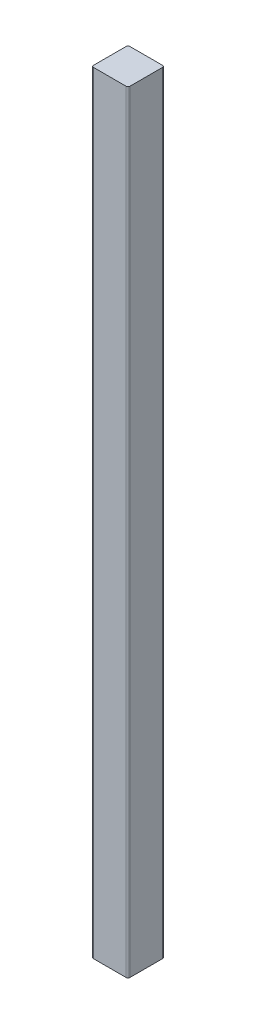
SolidWorks part; units mm, degrees
material "6063-O, Extruded Rod (SS)"
ref_plane "Front Plane" through (0, 0, 0) normal (0, 0, 1) x (1, 0, 0)
ref_plane "Top Plane" through (0, 0, 0) normal (0, 1, 0) x (1, 0, 0)
ref_plane "Right Plane" through (0, 0, 0) normal (1, 0, 0) x (0, 0, -1)
sketch "Sketch1" plane through (0, 0, 0) normal (0, 1, 0) x (1, 0, 0)
  line L1 (-18, 20) -> (18, 20)
  line L2 (-20, 18) -> (-20, -18)
  line L3 (-18, -20) -> (18, -20)
  line L4 (20, 18) -> (20, -18)
  line L5 (-20, 20) -> (20, -20) construction
  line L6 (-20, -20) -> (20, 20) construction
  arc A0 (-20, -18) -> (-18, -20) centre (-18, -18) ccw
  arc A1 (18, -20) -> (20, -18) centre (18, -18) ccw
  arc A2 (18, 20) -> (20, 18) centre (18, 18) cw
  arc A3 (-18, 20) -> (-20, 18) centre (-18, 18) ccw
  point P0 (0, 0)
  dimension "D3" = 2
  dimension "D1" = 40
  dimension "D2" = 40
extrude "Boss-Extrude1" add sketch "Sketch1" along normal blind 850
